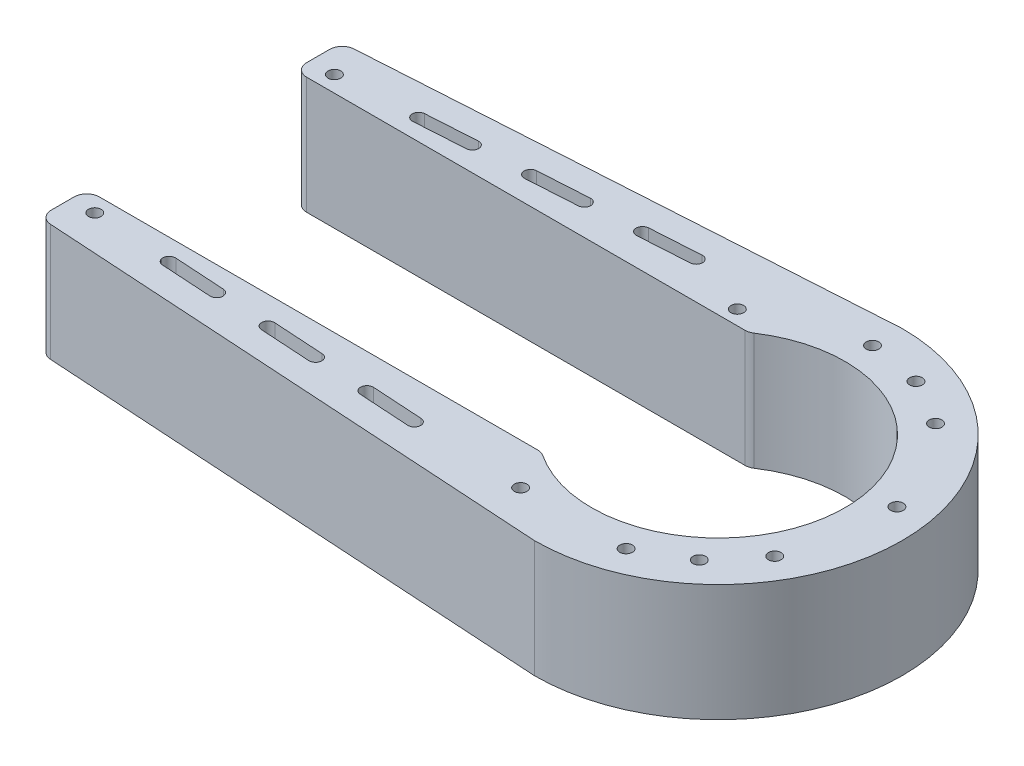
SolidWorks part; units mm, degrees
material "6061 合金"
ref_plane "前视基准面" through (0, 0, 0) normal (0, 0, 1) x (1, 0, 0)
ref_plane "上视基准面" through (0, 0, 0) normal (0, 1, 0) x (1, 0, 0)
ref_plane "右视基准面" through (0, 0, 0) normal (1, 0, 0) x (0, 0, -1)
other "Configuration Table"
sketch "草图1" plane through (0, 0, 0) normal (0, 1, 0) x (1, 0, 0)
  line L0 (0, -43.5) -> (0, 43.5) construction
  line L1 (0, 0) -> (-27.9613, 33.3229) construction
  line L2 (0, 0) -> (27.9613, 33.3229) construction
  line L3 (0, 0) -> (14.8779, 40.8766) construction
  line L4 (0, 0) -> (-250, 0) construction
  line L5 (-230.201, -19.799) -> (-269.799, 19.799) construction
  line L6 (-269.799, -19.799) -> (-230.201, 19.799) construction
  line L7 (0, 28) -> (-250, 28) construction
  line L8 (0, 28) -> (0, -28) construction
  line L9 (0, -28) -> (-250, -28) construction
  line L10 (-250, 28) -> (-250, -28) construction
  line L11 (-125, -28) -> (-125, 28) construction
  line L12 (0, 0) -> (-250, 0) construction
  line L13 (-250, 0) -> (-250, 18.6396) construction
  line L14 (-250, 0) -> (-236.565, 13.435) construction
  line L15 (-250, 0) -> (-263.435, 13.435) construction
  line L16 (-250, 28) -> (0, 43.5) construction
  line L17 (-250, -28) -> (0, -43.5) construction
  circle A0 centre (0, 0) radius 43.5 construction
  circle A1 centre (0, 0) radius 36.5 construction
  circle A2 centre (0, 0) radius 30 construction
  circle A7 centre (-23.4617, 27.9606) radius 1.25 construction
  circle A8 centre (0, 36.5) radius 1.25 construction
  circle A9 centre (12.4837, 34.2988) radius 1.5 construction
  circle A10 centre (23.4617, 27.9606) radius 1.25 construction
  circle A11 centre (35.9455, 6.3382) radius 1.25 construction
  circle A12 centre (31.6099, -18.25) radius 1.25 construction
  circle A13 centre (23.4617, -27.9606) radius 1.5 construction
  circle A14 centre (12.4837, -34.2988) radius 1.25 construction
  circle A15 centre (-12.4837, -34.2988) radius 1.25 construction
  circle A16 centre (-31.6099, -18.25) radius 1.25 construction
  circle A17 centre (-35.9455, -6.3382) radius 1.5 construction
  circle A18 centre (-35.9455, 6.3382) radius 1.25 construction
  circle A19 centre (-250, 0) radius 28 construction
  circle A20 centre (-250, 0) radius 22 construction
  circle A21 centre (-250, 0) radius 16 construction
  arc A22 (-263.435, 13.435) -> (-236.565, 13.435) centre (-250, 0) cw construction
  arc A23 (-234.4463, 15.5537) -> (-265.5537, 15.5537) centre (-250, 0) ccw construction
  arc A24 (-238.6836, 11.3164) -> (-261.3164, 11.3164) centre (-250, 0) ccw construction
  arc A25 (-238.6836, 11.3164) -> (-234.4463, 15.5537) centre (-236.565, 13.435) ccw construction
  arc A26 (-265.5537, 15.5537) -> (-261.3164, 11.3164) centre (-263.435, 13.435) ccw construction
  circle A27 centre (-250, 0) radius 4 construction
  circle A28 centre (-250, 4) radius 1.25 construction
  circle A29 centre (-254, 0) radius 1.25 construction
  circle A30 centre (-250, -4) radius 1.25 construction
  circle A31 centre (-246, 0) radius 1.25 construction
  arc A32 (-263.435, -13.435) -> (-236.565, -13.435) centre (-250, 0) ccw construction
  arc A33 (-234.4463, -15.5537) -> (-265.5537, -15.5537) centre (-250, 0) cw construction
  arc A34 (-238.6836, -11.3164) -> (-261.3164, -11.3164) centre (-250, 0) cw construction
  arc A35 (-238.6836, -11.3164) -> (-234.4463, -15.5537) centre (-236.565, -13.435) cw construction
  arc A36 (-265.5537, -15.5537) -> (-261.3164, -11.3164) centre (-263.435, -13.435) cw construction
  point P8 (0, 0)
  point P24 (-125, 0)
  point P42 (0, 0)
  point P44 (-250, 0)
  point P53 (-250, 19)
  point P71 (-250, -19)
  dimension "D1" = 3
ref_plane "基准面1" through (0, 5, 0) normal (0, 1, 0) x (1, 0, 0)
sketch "草图2" plane through (0, 5, 0) normal (0, 1, 0) x (1, 0, 0)
  line L0 (-250, 28) -> (0, 43.5)
  line L1 (-250, -28) -> (0, -43.5)
  arc A0 (-250, 28) -> (-250, -28) centre (-250, 0) ccw
  arc A1 (0, 43.5) -> (0, -43.5) centre (0, 0) cw
extrude "凸台-拉伸1" add sketch "草图2" along normal blind 27.7
sketch3d "3D草图1"
  point P0 (-145.9567, 32.7, -3.4646)
ref_plane "基准面2" through (0, 32.7, 0) normal (0, 1, 0) x (1, 0, 0)
sketch "草图3" plane through (0, 32.7, 0) normal (0, 1, 0) x (1, 0, 0)
  circle A0 centre (-250, 4) radius 1.25
  circle A1 centre (-246, 0) radius 1.25
  circle A2 centre (-250, -4) radius 1.25
  circle A3 centre (-254, 0) radius 1.25
  circle A4 centre (0, 0) radius 30
  circle A5 centre (0, 36.5) radius 1.5
  circle A6 centre (12.4837, 34.2988) radius 1.5
  circle A7 centre (23.4617, 27.9606) radius 1.5
  circle A8 centre (-23.4617, 27.9606) radius 1.5
  circle A9 centre (-35.9455, 6.3382) radius 1.5
  circle A10 centre (-35.9455, -6.3382) radius 1.5
  circle A11 centre (-31.6099, -18.25) radius 1.5
  circle A12 centre (-12.4837, -34.2988) radius 1.5
  circle A13 centre (12.4837, -34.2988) radius 1.5
  circle A14 centre (23.4617, -27.9606) radius 1.5
  circle A15 centre (31.6099, -18.25) radius 1.5
  circle A16 centre (35.9455, 6.3382) radius 1.5
  arc A17 (-265.5537, 15.5537) -> (-261.3164, 11.3164) centre (-263.435, 13.435) ccw
  arc A18 (-238.6836, 11.3164) -> (-234.4463, 15.5537) centre (-236.565, 13.435) ccw
  arc A19 (-234.4463, 15.5537) -> (-265.5537, 15.5537) centre (-250, 0) ccw
  arc A20 (-261.3164, 11.3164) -> (-238.6836, 11.3164) centre (-250, 0) cw
  arc A21 (-261.3164, -11.3164) -> (-238.6836, -11.3164) centre (-250, 0) ccw
  arc A22 (-234.4463, -15.5537) -> (-265.5537, -15.5537) centre (-250, 0) cw
  arc A23 (-265.5537, -15.5537) -> (-261.3164, -11.3164) centre (-263.435, -13.435) cw
  arc A24 (-238.6836, -11.3164) -> (-234.4463, -15.5537) centre (-236.565, -13.435) cw
extrude "切除-拉伸1" cut sketch "草图3" against normal blind 30
sketch3d "3D草图2"
  point P0 (-118.6358, 32.7, -10.1958)
ref_plane "基准面3" through (0, 32.7, 0) normal (0, 1, 0) x (1, 0, 0)
sketch "草图4" plane through (0, 32.7, 0) normal (0, 1, 0) x (1, 0, 0)
  line L0 (0, 0) -> (-250, 0) construction
  line L1 (-222.1049, 0) -> (-217.1049, 0) construction
  line L3 (-217.1049, 0) -> (-210.1249, -4.0299) construction
  line L4 (-217.1049, 0) -> (-205.2675, 20.5031) construction
  line L5 (-205.2675, 20.5031) -> (-198.2874, 16.4731) construction
  line L6 (-210.1249, -4.0299) -> (-198.2874, 16.4731) construction
  line L7 (-217.1049, 0) -> (-198.2874, 16.4731) construction
  line L8 (-205.2675, 20.5031) -> (-210.1249, -4.0299) construction
  line L28 (-214.6027, 0) -> (-194.6027, 0) construction
  line L29 (-115.7976, 0) -> (-43.3199, 0) construction
  line L30 (-216.2389, 1.5) -> (-205.2675, 20.5031)
  line L31 (-54.444, 1.5) -> (-65.7024, 21)
  line L32 (-68.3004, 22.5) -> (-90.8171, 22.5)
  line L33 (-93.4152, 21) -> (-104.6735, 1.5)
  line L34 (-104.6735, -1.5) -> (-93.4152, -21)
  line L35 (-90.8171, -22.5) -> (-68.3004, -22.5)
  line L36 (-65.7024, -21) -> (-54.444, -1.5)
  line L37 (-206.9322, 1.5) -> (-198.2874, 16.4731)
  line L38 (-206.9322, -1.5) -> (-198.2874, -16.4731)
  line L39 (-216.2389, -1.5) -> (-205.2675, -20.5031)
  line L40 (-188.9322, -1.5) -> (-180.2874, -16.4731)
  line L41 (-198.2389, -1.5) -> (-187.2675, -20.5031)
  line L42 (-198.2389, 1.5) -> (-187.2675, 20.5031)
  line L43 (-188.9322, 1.5) -> (-180.2874, 16.4731)
  line L44 (-170.9322, -1.5) -> (-162.2874, -16.4731)
  line L45 (-180.2389, -1.5) -> (-169.2675, -20.5031)
  line L46 (-180.2389, 1.5) -> (-169.2675, 20.5031)
  line L47 (-170.9322, 1.5) -> (-162.2874, 16.4731)
  line L48 (-152.9322, -1.5) -> (-144.2874, -16.4731)
  line L49 (-162.2389, -1.5) -> (-151.2675, -20.5031)
  line L50 (-162.2389, 1.5) -> (-151.2675, 20.5031)
  line L51 (-152.9322, 1.5) -> (-144.2874, 16.4731)
  line L52 (-134.9322, -1.5) -> (-126.2874, -16.4731)
  line L53 (-144.2389, -1.5) -> (-133.2675, -20.5031)
  line L54 (-144.2389, 1.5) -> (-133.2675, 20.5031)
  line L55 (-134.9322, 1.5) -> (-126.2874, 16.4731)
  line L56 (-116.9322, -1.5) -> (-108.2874, -16.4731)
  line L57 (-126.2389, -1.5) -> (-115.2675, -20.5031)
  line L58 (-126.2389, 1.5) -> (-115.2675, 20.5031)
  line L59 (-116.9322, 1.5) -> (-108.2874, 16.4731)
  line L60 (-206.9322, -1.5) -> (-188.9322, -1.5) construction
  arc A0 (-205.2675, 20.5031) -> (-198.2874, 16.4731) centre (-201.7775, 18.4881) cw construction
  circle A21 centre (-79.5588, 0) radius 22.5 construction
  arc A22 (-93.4152, 21) -> (-90.8171, 22.5) centre (-90.8171, 19.5) cw
  arc A23 (-104.6735, -1.5) -> (-104.6735, 1.5) centre (-102.0754, 0) cw
  arc A24 (-90.8171, -22.5) -> (-93.4152, -21) centre (-90.8171, -19.5) cw
  arc A25 (-65.7024, -21) -> (-68.3004, -22.5) centre (-68.3004, -19.5) cw
  arc A26 (-54.444, 1.5) -> (-54.444, -1.5) centre (-57.0421, 0) cw
  arc A27 (-65.7024, 21) -> (-68.3004, 22.5) centre (-68.3004, 19.5) ccw
  arc A28 (-205.2675, 20.5031) -> (-198.2874, 16.4731) centre (-201.7775, 18.4881) cw
  arc A29 (-205.2675, -20.5031) -> (-198.2874, -16.4731) centre (-201.7775, -18.4881) ccw
  arc A30 (-216.2389, -1.5) -> (-216.2389, 1.5) centre (-213.6408, 0) cw
  arc A31 (-206.9322, -1.5) -> (-206.9322, 1.5) centre (-204.3341, 0) cw
  arc A32 (-188.9322, -1.5) -> (-188.9322, 1.5) centre (-186.3341, 0) cw
  arc A33 (-187.2675, -20.5031) -> (-180.2874, -16.4731) centre (-183.7775, -18.4881) ccw
  arc A34 (-198.2389, -1.5) -> (-198.2389, 1.5) centre (-195.6408, 0) cw
  arc A35 (-187.2675, 20.5031) -> (-180.2874, 16.4731) centre (-183.7775, 18.4881) cw
  arc A36 (-170.9322, -1.5) -> (-170.9322, 1.5) centre (-168.3341, 0) cw
  arc A37 (-169.2675, -20.5031) -> (-162.2874, -16.4731) centre (-165.7775, -18.4881) ccw
  arc A38 (-180.2389, -1.5) -> (-180.2389, 1.5) centre (-177.6408, 0) cw
  arc A39 (-169.2675, 20.5031) -> (-162.2874, 16.4731) centre (-165.7775, 18.4881) cw
  arc A40 (-152.9322, -1.5) -> (-152.9322, 1.5) centre (-150.3341, 0) cw
  arc A41 (-151.2675, -20.5031) -> (-144.2874, -16.4731) centre (-147.7775, -18.4881) ccw
  arc A42 (-162.2389, -1.5) -> (-162.2389, 1.5) centre (-159.6408, 0) cw
  arc A43 (-151.2675, 20.5031) -> (-144.2874, 16.4731) centre (-147.7775, 18.4881) cw
  arc A44 (-134.9322, -1.5) -> (-134.9322, 1.5) centre (-132.3341, 0) cw
  arc A45 (-133.2675, -20.5031) -> (-126.2874, -16.4731) centre (-129.7775, -18.4881) ccw
  arc A46 (-144.2389, -1.5) -> (-144.2389, 1.5) centre (-141.6408, 0) cw
  arc A47 (-133.2675, 20.5031) -> (-126.2874, 16.4731) centre (-129.7775, 18.4881) cw
  arc A48 (-116.9322, -1.5) -> (-116.9322, 1.5) centre (-114.3341, 0) cw
  arc A49 (-115.2675, -20.5031) -> (-108.2874, -16.4731) centre (-111.7775, -18.4881) ccw
  arc A50 (-126.2389, -1.5) -> (-126.2389, 1.5) centre (-123.6408, 0) cw
  arc A51 (-115.2675, 20.5031) -> (-108.2874, 16.4731) centre (-111.7775, 18.4881) cw
  point P19 (-207.7982, 0)
  point P23 (-207.7982, 0)
  dimension "D2" = 3
  dimension "D5" = 3
  dimension "D6" = 3
  dimension "D7" = 3
  dimension "D8" = 3
  dimension "D9" = 3
  dimension "D10" = 3
  dimension "D11" = 18
  dimension "D3" = 3
  dimension "D4" = 6
extrude "切除-拉伸2" cut sketch "草图4" against normal blind 3
ref_plane "基准面4" through (0, 32.7, 0) normal (0, 1, 0) x (1, 0, 0)
sketch "草图5" plane through (0, 32.7, 0) normal (0, 1, 0) x (1, 0, 0)
  line L0 (-125, 0) -> (-43.5, 0) construction
  line L5 (-125, 28) -> (-27.1878, 34.0644) construction
  line L6 (0, 0) -> (-250, 0) construction
  line L11 (-250, 28) -> (0, 43.5) construction
  circle A3 centre (-44.9417, 32.9636) radius 1.25
  circle A4 centre (-69.7029, 31.4284) radius 1.25
  circle A7 centre (-119.2253, 28.358) radius 1.5
  circle A8 centre (-94.4641, 29.8932) radius 1.25
  circle A9 centre (0, 0) radius 43.5 construction
  circle A10 centre (-44.9417, -32.9636) radius 1.25
  circle A11 centre (-69.7029, -31.4284) radius 1.25
  circle A12 centre (-94.4641, -29.8932) radius 1.25
  circle A13 centre (-119.2253, -28.358) radius 1.5
  point P3 (-62.5299, 31.5812)
  point P4 (-62.5299, 31.5812)
extrude "切除-拉伸3" cut sketch "草图5" against normal blind 30
sketch3d "3D草图3"
  point P0 (-170.9019, 32.7, -25.8361)
ref_plane "基准面5" through (0, 32.7, 0) normal (0, 1, 0) x (1, 0, 0)
sketch "草图6" plane through (0, 32.7, 0) normal (0, 1, 0) x (1, 0, 0)
  line L1 (-281.6754, 38.6339) -> (-124.9483, 38.6339)
  line L2 (-281.6754, 38.6339) -> (-281.6754, -38.6174)
  line L3 (-281.6754, -38.6174) -> (-124.9483, -38.6174)
  line L4 (-124.9483, 38.6339) -> (-124.9483, -38.6174)
  line L5 (-281.6754, 38.6339) -> (-124.9483, -38.6174) construction
  line L6 (-281.6754, -38.6174) -> (-124.9483, 38.6339) construction
  point P4 (-203.3119, 0.0082)
extrude "切除-拉伸4" cut sketch "草图6" against normal blind 36
sketch3d "3D草图4"
  point P0 (-50.5315, 32.7, -14.5263)
ref_plane "基准面6" through (0, 32.7, 0) normal (0, 1, 0) x (1, 0, 0)
sketch "草图7" plane through (0, 32.7, 0) normal (0, 1, 0) x (1, 0, 0)
  line L0 (-111.7775, 22.518) -> (-19.8227, 22.518) construction
  line L1 (-111.7775, -22.518) -> (-37.2181, -22.518) construction
  line L2 (-125, -28) -> (-125, 28) construction
  line L3 (-125, 22.518) -> (-19.8227, 22.518) construction
  line L4 (-125, 22.518) -> (-125, -22.518) construction
  line L5 (-125, -22.518) -> (-19.8227, -22.518) construction
  line L6 (-19.8227, 22.518) -> (-19.8227, -22.518) construction
  line L7 (-125, 22.518) -> (-19.8227, -22.518) construction
  line L8 (-125, -22.518) -> (-19.8227, 22.518) construction
  line L10 (-127.5572, 24.5337) -> (-17.2655, 24.5337)
  line L11 (-127.5572, 24.5337) -> (-127.5572, -24.5337)
  line L12 (-127.5572, -24.5337) -> (-17.2655, -24.5337)
  line L13 (-17.2655, 24.5337) -> (-17.2655, -24.5337)
  line L14 (-127.5572, 24.5337) -> (-17.2655, -24.5337) construction
  line L15 (-127.5572, -24.5337) -> (-17.2655, 24.5337) construction
  circle A0 centre (0, 0) radius 30 construction
  circle A5 centre (0, 0) radius 30 construction
  point P6 (-72.4113, 0)
  point P14 (-72.4113, 0)
extrude "切除-拉伸5" cut sketch "草图7" against normal blind 36
fillet "圆角1" radius 3 1 edges at (-124.9483, 18.85, -35.7532)
ref_plane "基准面7" through (0, 32.7, 0) normal (0, 1, 0) x (1, 0, 0)
sketch "草图8" plane through (0, 32.7, 0) normal (0, 1, 0) x (1, 0, 0)
  line L0 (-119.2253, 28.358) -> (-69.7029, 31.4284) construction
  line L1 (-100.4526, 29.5219) -> (-88.4756, 30.2645) construction
  line L2 (-100.5454, 31.0191) -> (-88.5684, 31.7616)
  line L3 (-100.3598, 28.0248) -> (-88.3828, 28.7674)
  line L4 (-75.4077, 29.5718) -> (-63.4307, 30.3144)
  line L5 (-75.5933, 32.5661) -> (-63.6163, 33.3087)
  line L6 (-75.5005, 31.069) -> (-63.5235, 31.8115) construction
  line L7 (-50.6412, 34.1131) -> (-38.6642, 34.8557)
  line L8 (-50.4556, 31.1189) -> (-38.4786, 31.8614)
  line L9 (-50.5484, 32.616) -> (-38.5714, 33.3586) construction
  line L10 (0, 0) -> (-101.4347, 0) construction
  line L11 (-50.5484, -32.616) -> (-38.5714, -33.3586) construction
  line L12 (-50.6412, -34.1131) -> (-38.6642, -34.8557)
  line L13 (-50.4556, -31.1189) -> (-38.4786, -31.8614)
  line L14 (-75.5005, -31.069) -> (-63.5235, -31.8115) construction
  line L15 (-75.5933, -32.5661) -> (-63.6163, -33.3087)
  line L16 (-75.4077, -29.5718) -> (-63.4307, -30.3144)
  line L17 (-100.4526, -29.5219) -> (-88.4756, -30.2645) construction
  line L18 (-100.5454, -31.0191) -> (-88.5684, -31.7616)
  line L19 (-100.3598, -28.0248) -> (-88.3828, -28.7674)
  line L20 (-119.2253, -28.358) -> (-69.7029, -31.4284) construction
  arc A0 (-100.5454, 31.0191) -> (-100.3598, 28.0248) centre (-100.4526, 29.5219) ccw
  arc A1 (-88.3828, 28.7674) -> (-88.5684, 31.7616) centre (-88.4756, 30.2645) ccw
  arc A2 (-75.5933, 32.5661) -> (-75.4077, 29.5718) centre (-75.5005, 31.069) ccw
  arc A3 (-63.4307, 30.3144) -> (-63.6163, 33.3087) centre (-63.5235, 31.8115) ccw
  arc A4 (-38.4786, 31.8614) -> (-38.6642, 34.8557) centre (-38.5714, 33.3586) ccw
  arc A5 (-50.6412, 34.1131) -> (-50.4556, 31.1189) centre (-50.5484, 32.616) ccw
  arc A6 (-50.6412, -34.1131) -> (-50.4556, -31.1189) centre (-50.5484, -32.616) cw
  arc A7 (-38.4786, -31.8614) -> (-38.6642, -34.8557) centre (-38.5714, -33.3586) cw
  arc A8 (-75.5933, -32.5661) -> (-75.4077, -29.5718) centre (-75.5005, -31.069) cw
  arc A9 (-63.4307, -30.3144) -> (-63.6163, -33.3087) centre (-63.5235, -31.8115) cw
  arc A10 (-100.5454, -31.0191) -> (-100.3598, -28.0248) centre (-100.4526, -29.5219) cw
  arc A11 (-88.3828, -28.7674) -> (-88.5684, -31.7616) centre (-88.4756, -30.2645) cw
  point P5 (-94.4641, 29.8932)
  point P7 (-94.4641, 29.8932)
  point P15 (-69.512, 31.4403)
  point P22 (-44.5599, 32.9873)
  point P30 (-44.5599, -32.9873)
  point P37 (-69.512, -31.4403)
  point P44 (-94.4641, -29.8932)
  dimension "D1" = 2
  dimension "D2" = 2
extrude "切除-拉伸6" cut sketch "草图8" against normal blind 40
sketch3d "3D草图5"
  point P0 (-61.6107, 20.4017, 39.6801)
ref_plane "基准面8" through (-2.6867, 0, 43.3334) normal (-0.0619, 0, 0.9981) x (0.9981, 0, 0.0619)
sketch "草图9" plane through (-2.6867, 0, 43.3334) normal (-0.0619, 0, 0.9981) x (0.9981, 0, 0.0619)
  line L0 (-115.6767, 9) -> (-115.6767, 28.7) construction
  line L5 (-115.6767, 28.7) -> (-1.3082, 28.7) construction
  line L6 (-1.3082, 9) -> (-1.3082, 28.7) construction
  line L7 (-115.6767, 9) -> (-1.3082, 9) construction
  line L8 (-55.6767, 25.7) -> (-55.6767, 12)
  line L9 (-112.6767, 28.7) -> (-82.6767, 28.7)
  line L10 (-115.6767, 25.7) -> (-115.6767, 12)
  line L11 (-112.6767, 9) -> (-82.6767, 9)
  line L12 (-79.6767, 25.7) -> (-79.6767, 12)
  line L13 (-52.6767, 28.7) -> (-22.6767, 28.7)
  line L14 (-19.6767, 25.7) -> (-19.6767, 12)
  line L15 (-52.6767, 9) -> (-22.6767, 9)
  arc A0 (-82.6767, 28.7) -> (-79.6767, 25.7) centre (-82.6767, 25.7) cw
  arc A1 (-79.6767, 12) -> (-82.6767, 9) centre (-82.6767, 12) cw
  arc A2 (-112.6767, 9) -> (-115.6767, 12) centre (-112.6767, 12) cw
  arc A3 (-115.6767, 25.7) -> (-112.6767, 28.7) centre (-112.6767, 25.7) cw
  arc A4 (-55.6767, 25.7) -> (-52.6767, 28.7) centre (-52.6767, 25.7) cw
  arc A5 (-52.6767, 9) -> (-55.6767, 12) centre (-52.6767, 12) cw
  arc A6 (-22.6767, 28.7) -> (-19.6767, 25.7) centre (-22.6767, 25.7) cw
  arc A7 (-19.6767, 12) -> (-22.6767, 9) centre (-22.6767, 12) cw
  point P12 (-79.6767, 9)
  dimension "D1" = 3
  dimension "D2" = 2
fillet "圆角2" radius 3 5 edges at (-124.9483, 18.85, 35.7532) (-124.9483, 18.85, 24.5337) (-17.2655, 18.85, 24.5337) (-17.2655, 18.85, -24.5337) (-124.9483, 18.85, -24.5337)
